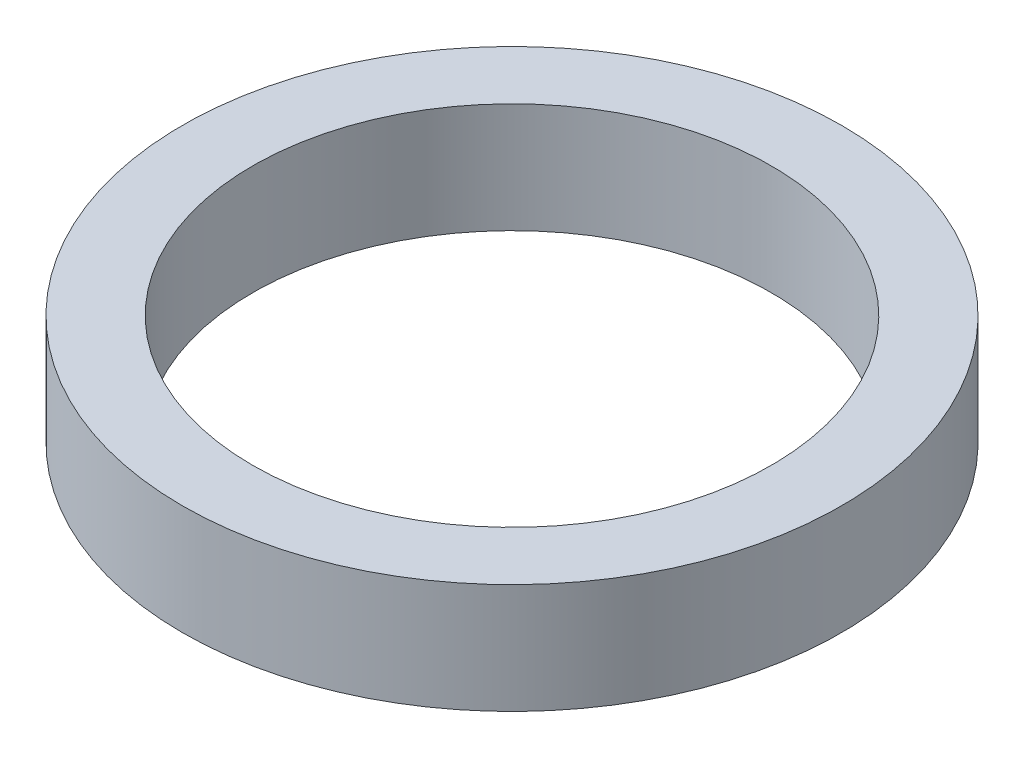
SolidWorks part; units mm, degrees
ref_plane "Front Plane" through (0, 0, 0) normal (0, 0, 1) x (1, 0, 0)
ref_plane "Top Plane" through (0, 0, 0) normal (0, 1, 0) x (1, 0, 0)
ref_plane "Right Plane" through (0, 0, 0) normal (1, 0, 0) x (0, 0, -1)
sketch "Sketch1" plane through (0, 0, 0) normal (0, 1, 0) x (1, 0, 0)
  circle A0 centre (0, 0) radius 5.4
  circle A1 centre (0, 0) radius 4.25
  dimension "D1" = 8.5
  dimension "D2" = 10.8
extrude "Boss-Extrude1" add sketch "Sketch1" along normal blind 1.8
